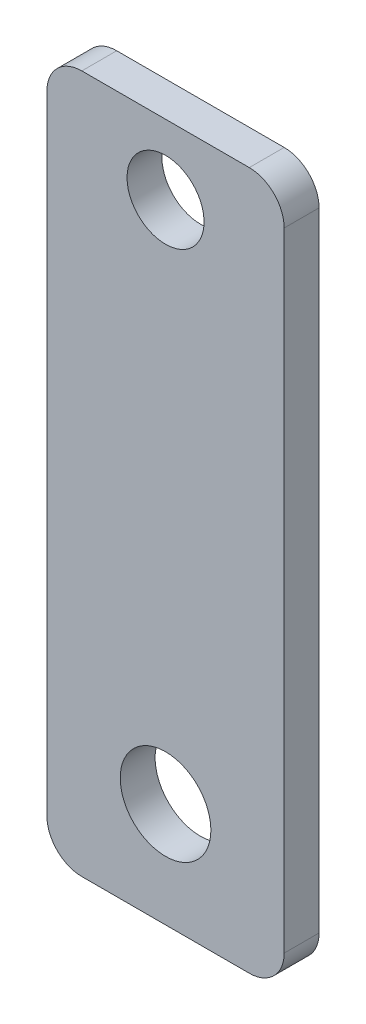
SolidWorks part; units mm, degrees
material "3003 Alloy"
ref_plane "X-Y Datum" through (0, 0, 0) normal (0, 0, 1) x (1, 0, 0)
ref_plane "X-Z Datum" through (0, 0, 0) normal (0, 1, 0) x (1, 0, 0)
ref_plane "Y-Z Datum" through (0, 0, 0) normal (1, 0, 0) x (0, 0, -1)
sketch "Sketch1" plane through (0, 0, 0) normal (0, 0, 1) x (1, 0, 0)
  line L0 (10.795, 32.0197) -> (10.795, 29.368) construction
  line L1 (0, 0) -> (21.59, 0)
  line L2 (0, 0) -> (0, 63.5)
  line L3 (0, 63.5) -> (21.59, 63.5)
  line L4 (21.59, 0) -> (21.59, 63.5)
  line L5 (0, 33.3375) -> (19.6604, 33.3375) construction
  circle A0 centre (10.795, 9.525) radius 4.125
  circle A1 centre (10.795, 57.15) radius 3.5052
  circle A4 centre (10.795, 117.1448) radius 3.5052 construction
  circle A5 centre (19.4521, 329.1192) radius 4.125 construction
  dimension "D2" = 6.35
  dimension "D1" = 63.5
  dimension "D3" = 9.525
extrude "Boss-Extrude1" add sketch "Sketch1" along normal blind 3.175 contours L0 A0 | A0 L0 | L3 L4 L1 L2 | A1
fillet "Fillet1" radius 3.175 4 edges at (21.59, 63.5, 1.5875) (0, 63.5, 1.5875) (0, 0, 1.5875) (21.59, 0, 1.5875)
